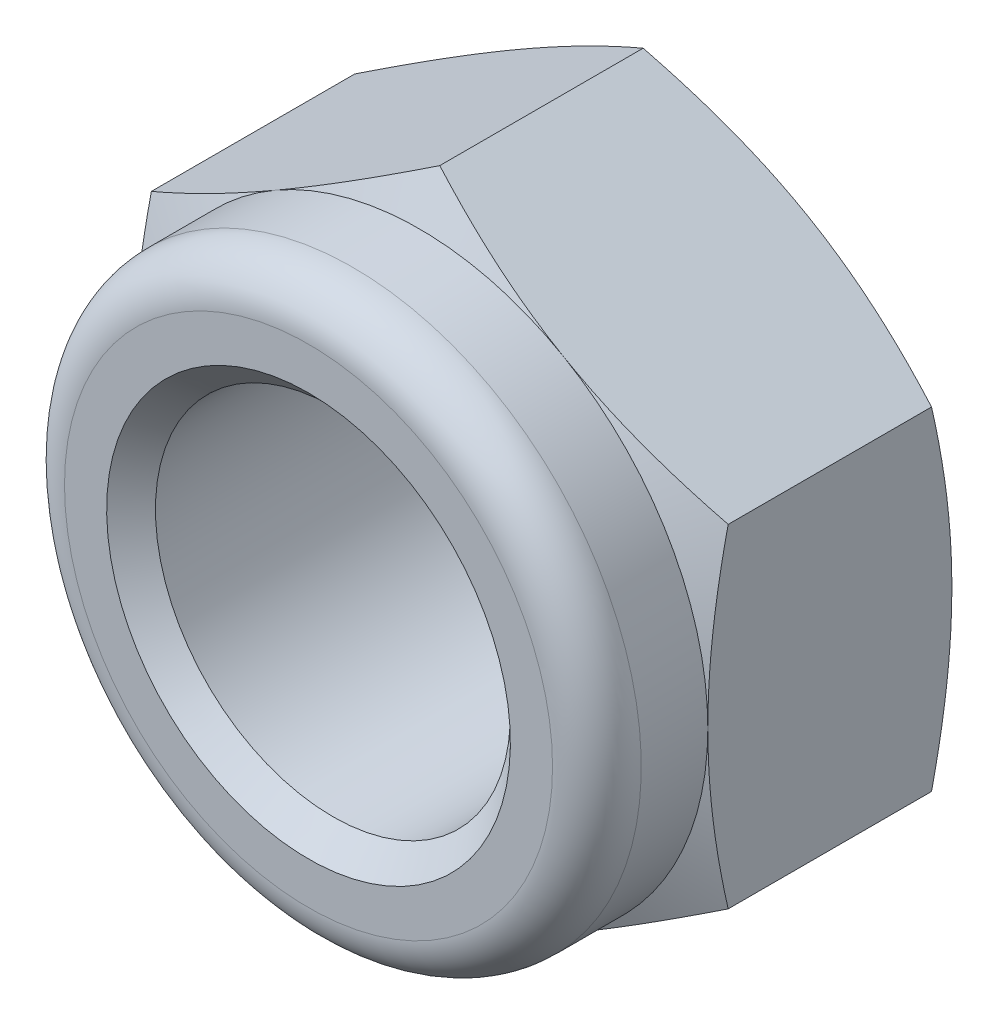
SolidWorks part; units mm, degrees
material "Plain Carbon Steel"
ref_plane "Front Plane" through (0, 0, 0) normal (0, 0, 1) x (1, 0, 0)
ref_plane "Top Plane" through (0, 0, 0) normal (0, 1, 0) x (1, 0, 0)
ref_plane "Right Plane" through (0, 0, 0) normal (1, 0, 0) x (0, 0, -1)
sketch "Sketch1" plane through (0, 0, 0) normal (0, 0, 1) x (1, 0, 0)
  line L1 (0, -7.5056) -> (6.5, -3.7528)
  line L2 (6.5, -3.7528) -> (6.5, 3.7528)
  line L3 (6.5, 3.7528) -> (0, 7.5056)
  line L4 (0, 7.5056) -> (-6.5, 3.7528)
  line L5 (-6.5, 3.7528) -> (-6.5, -3.7528)
  line L6 (-6.5, -3.7528) -> (0, -7.5056)
  circle A0 centre (0, 0) radius 6.5 construction
  circle A1 centre (0, 0) radius 4
  dimension "D2" = 8
  dimension "D1" = 13
extrude "Boss-Extrude1" add sketch "Sketch1" along normal blind 5.5
sketch "Sketch3" plane through (0, 0, 0) normal (0, 1, 0) x (0, 0, -1)
  line L0 (-5.5, 6.5) -> (-7, 6.5)
  line L1 (-5.5, -6.5) -> (-5.5, 0) construction
  line L2 (-8, 5.5) -> (-8, 4)
  line L3 (-8, 4) -> (-5.5, 4)
  line L5 (-5.5, 4) -> (-5.5, 6.5)
  line L6 (0, 0) -> (-2.4, 0) construction
  arc A0 (-7, 6.5) -> (-8, 5.5) centre (-7, 5.5) ccw
  dimension "D1" = 1
  dimension "D2" = 8
revolve "Revolve1" add sketch "Sketch3" angle 360 about L6
sketch "Sketch2" plane through (0, 0, 0) normal (1, 0, 0) x (0, 0, -1)
  line L0 (-5.5, 7.5056) -> (-5.5, 6.5)
  line L1 (-5.5, 3.7528) -> (-5.5, 5.6292) construction
  line L2 (-5.5, 6.5) -> (-5.0417, 7.5056)
  line L3 (-5.5, 7.5056) -> (0, 7.5056) construction
  line L4 (-5.0417, 7.5056) -> (-5.5, 7.5056)
  line L5 (-0.4583, 7.5056) -> (0, 7.5056)
  line L6 (0, 7.5056) -> (0, 6.5)
  line L7 (0, 3.7528) -> (0, 7.5056) construction
  line L8 (0, 6.5) -> (-0.4583, 7.5056)
  line L9 (-5.0417, 7.5056) -> (-4.5833, 7.5056) construction
  line L10 (-4.5833, 7.5056) -> (-4.125, 7.5056) construction
  line L11 (-4.125, 7.5056) -> (-3.6667, 7.5056) construction
  line L12 (-3.6667, 7.5056) -> (-3.2083, 7.5056) construction
  line L13 (-3.2083, 7.5056) -> (-2.75, 7.5056) construction
  line L14 (-2.75, 7.5056) -> (-2.2917, 7.5056) construction
  line L15 (-2.2917, 7.5056) -> (-1.8333, 7.5056) construction
  line L16 (-1.8333, 7.5056) -> (-1.375, 7.5056) construction
  line L17 (-1.375, 7.5056) -> (-0.9167, 7.5056) construction
  line L18 (0, 0) -> (-2.4, 0) construction
  line L20 (-8, 4) -> (-7.45, 4)
  line L21 (-7.45, 4) -> (-8, 4.55)
  line L22 (-8, 4.55) -> (-8, 4)
  line L23 (0, 4) -> (-0.55, 4)
  line L24 (0, -3.7528) -> (0, 3.7528) construction
  line L25 (-0.55, 4) -> (0, 4.55)
  line L26 (0, 4.55) -> (0, 4)
  line L27 (-8, 5.5) -> (-8, -5.5) construction
  line L28 (-4.4, 4) -> (-4.95, 4) construction
  line L29 (-4.95, 4) -> (-5.5, 4) construction
  line L30 (-4.4, 4) -> (-3.85, 4) construction
  line L31 (-3.85, 4) -> (-3.3, 4) construction
  line L32 (-3.3, 4) -> (-2.75, 4) construction
  line L33 (-2.75, 4) -> (-2.2, 4) construction
  line L34 (-2.2, 4) -> (-1.65, 4) construction
  line L35 (-1.65, 4) -> (-1.1, 4) construction
  line L36 (-1.1, 4) -> (-0.55, 4) construction
  line L37 (-0.9167, 7.5056) -> (-0.4583, 7.5056) construction
  line L38 (-5.5, 0) -> (-5.5, 3.7528) construction
  dimension "D1" = 13
revolve "Cut-Revolve1" cut sketch "Sketch2" angle 360 about L18
